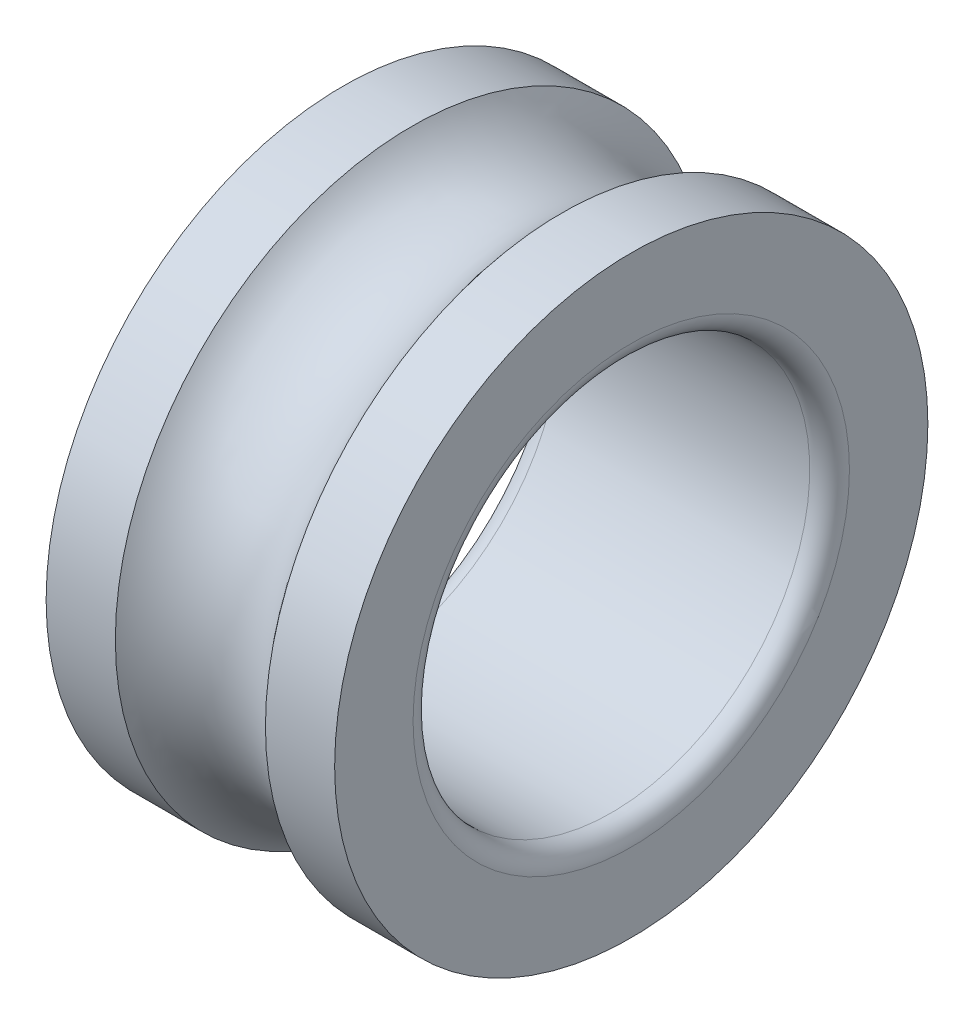
SolidWorks part; units mm, degrees
ref_plane "Front Plane" through (0, 0, 0) normal (0, 0, 1) x (1, 0, 0)
ref_plane "Top Plane" through (0, 0, 0) normal (0, 1, 0) x (1, 0, 0)
ref_plane "Right Plane" through (0, 0, 0) normal (1, 0, 0) x (0, 0, -1)
ref_plane "Plane1"
sketch "Sketch1" plane through (0, 0, 0) normal (0, 0, 1) x (1, 0, 0)
  line L0 (1.1, 11) -> (14.9, 11)
  line L1 (16, 12.1) -> (16, 16.45)
  line L2 (16, 16.45) -> (12.1615, 16.45)
  line L3 (3.8385, 16.45) -> (0, 16.45)
  line L4 (0, 16.45) -> (0, 12.1)
  line L5 (50, 0) -> (-50, 0) construction
  arc A0 (0, 12.1) -> (1.1, 11) centre (1.1, 12.1) ccw
  arc A1 (14.9, 11) -> (16, 12.1) centre (14.9, 12.1) ccw
  arc A2 (3.8385, 16.45) -> (12.1615, 16.45) centre (8, 19.5) ccw
revolve "Revolução1" add sketch "Sketch1" angle 360 about L5
